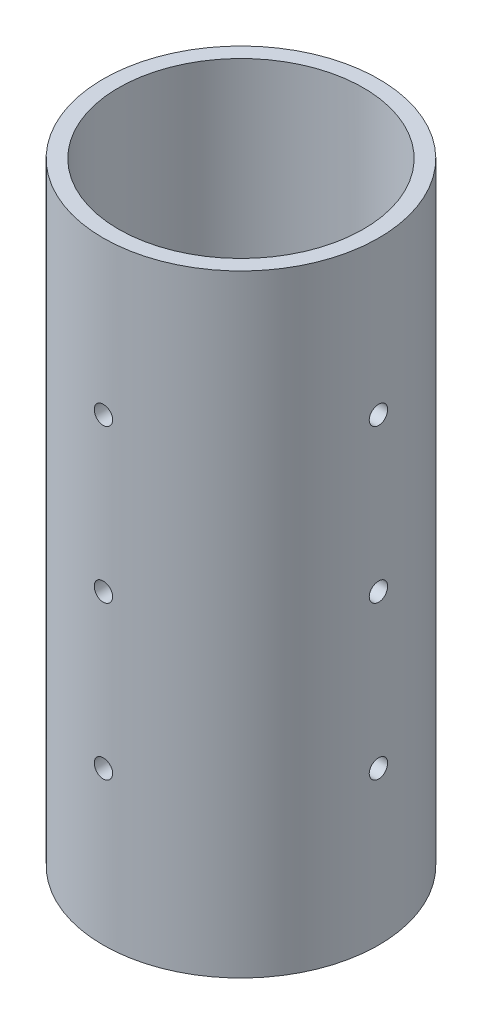
SolidWorks part; units mm, degrees
ref_plane "Front Plane" through (0, 0, 0) normal (0, 0, 1) x (1, 0, 0)
ref_plane "Top Plane" through (0, 0, 0) normal (0, 1, 0) x (1, 0, 0)
ref_plane "Right Plane" through (0, 0, 0) normal (1, 0, 0) x (0, 0, -1)
sketch "Sketch1" plane through (0, 0, 0) normal (0, 1, 0) x (1, 0, 0)
  circle A0 centre (0, 0) radius 22.5
  dimension "D1" = 45
extrude "Boss-Extrude1" add sketch "Sketch1" along normal blind 100
hole_wizard "Tap Drill for M6x1.0 Tap4" positions "3DSketch8" profile "Sketch8" hole size "M6x1.0" standard "ANSI Metric" end condition through all
sketch3d "3DSketch8"
  point P0 (0, 25, 22.5)
sketch "Sketch8" plane through (0, 25, 22.5) normal (1, 0, 0) x (0, -1, 0)
  line L0 (0, 0) -> (0, 45)
  line L1 (0, 45) -> (1.5, 45)
  line L2 (1.5, 45) -> (1.5, 0)
  line L5 (1.5, 0) -> (0, 0)
  line L11 (0, -6.35) -> (0, 107.95) construction
  dimension "Thru Hole Dia." = 3
  dimension "Thru Hole Depth" = 45
hole_wizard "Tap Drill for M6x1.0 Tap5" positions "3DSketch9" profile "Sketch9" hole size "M6x1.0" standard "ANSI Metric" end condition through all
sketch3d "3DSketch9"
  point P0 (-22.5, 25, 0)
sketch "Sketch9" plane through (-22.5, 25, 0) normal (0, 1, 0) x (0, 0, 1)
  line L0 (0, 0) -> (0, 45)
  line L1 (0, 45) -> (1.5, 45)
  line L2 (1.5, 45) -> (1.5, 0)
  line L5 (1.5, 0) -> (0, 0)
  line L11 (0, -6.35) -> (0, 107.95) construction
  dimension "Thru Hole Dia." = 3
  dimension "Thru Hole Depth" = 45
hole_wizard "Tap Drill for M6x1.0 Tap6" positions "3DSketch10" profile "Sketch10" hole size "M6x1.0" standard "ANSI Metric" end condition through all
sketch3d "3DSketch10"
  point P0 (-22.5, 50, 0)
  point P2 (0, 50, 22.5)
sketch "Sketch10" plane through (-22.5, 50, 0) normal (0, 1, 0) x (0, 0, 1)
  line L0 (0, 0) -> (0, 45)
  line L1 (0, 45) -> (1.5, 45)
  line L2 (1.5, 45) -> (1.5, 0)
  line L5 (1.5, 0) -> (0, 0)
  line L11 (0, -6.35) -> (0, 107.95) construction
  dimension "Thru Hole Dia." = 3
  dimension "Thru Hole Depth" = 45
hole_wizard "Tap Drill for M6x1.0 Tap7" positions "3DSketch11" profile "Sketch11" hole size "M6x1.0" standard "ANSI Metric" end condition through all
sketch3d "3DSketch11"
  point P0 (0, 75, 22.5)
  point P2 (-22.5, 75, 0)
sketch "Sketch11" plane through (0, 75, 22.5) normal (1, 0, 0) x (0, -1, 0)
  line L0 (0, 0) -> (0, 45)
  line L1 (0, 45) -> (1.5, 45)
  line L2 (1.5, 45) -> (1.5, 0)
  line L5 (1.5, 0) -> (0, 0)
  line L11 (0, -6.35) -> (0, 107.95) construction
  dimension "Thru Hole Dia." = 3
  dimension "Thru Hole Depth" = 45
sketch "Sketch12" plane through (0, 100, 0) normal (0, 1, 0) x (1, 0, 0)
  circle A0 centre (0, 0) radius 20
  dimension "D1" = 40
extrude "Cut-Extrude1" cut sketch "Sketch12" against normal blind 90
sketch "Sketch15" plane through (0, 0, 0) normal (0, -1, 0) x (1, 0, 0)
  circle A0 centre (0, -3.5) radius 2.5
  circle A1 centre (0, 11.5) radius 2.5
  point P0 (0, 0)
  point P5 (0, 11.5)
  point P9 (0, -3.5)
  dimension "D1" = 5
  dimension "D2" = 15
extrude "Cut-Extrude2" cut sketch "Sketch15" against normal blind 90
